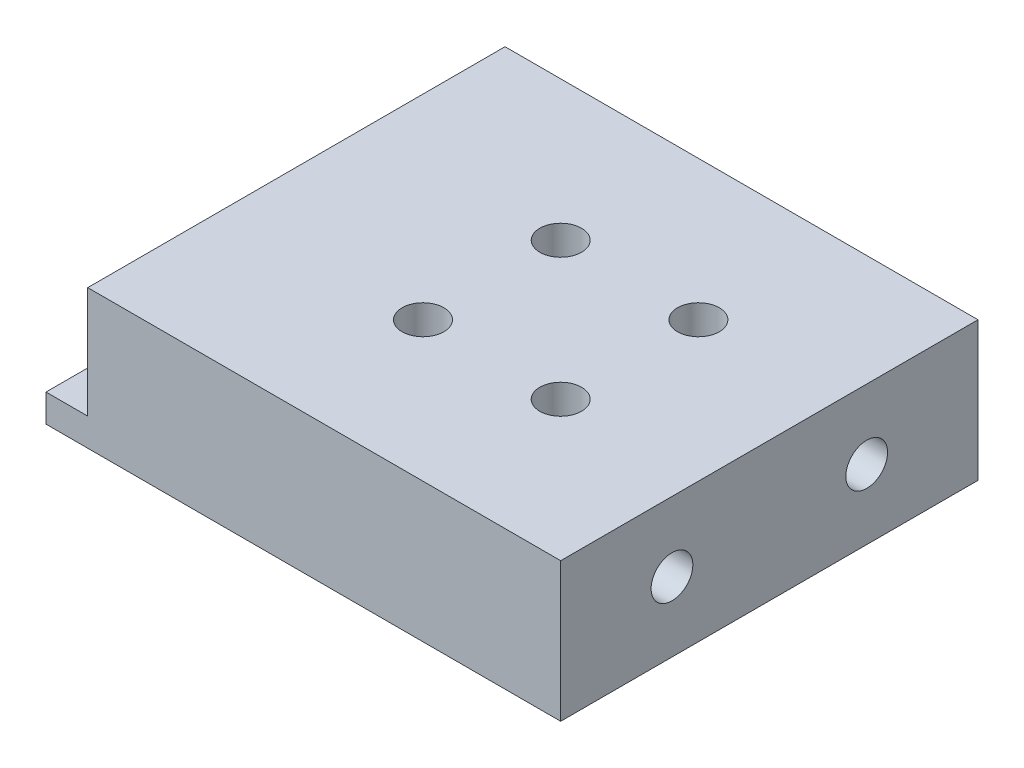
SolidWorks part; units mm, degrees
ref_plane "Спереди" through (0, 0, 0) normal (0, 0, 1) x (1, 0, 0)
ref_plane "Сверху" through (0, 0, 0) normal (0, 1, 0) x (1, 0, 0)
ref_plane "Справа" through (0, 0, 0) normal (1, 0, 0) x (0, 0, -1)
sketch "Эскиз1" plane through (0, 0, 0) normal (0, 1, 0) x (1, 0, 0)
  line L0 (22, 15) -> (15.9896, 21.0104) construction
  line L1 (0, 0) -> (37, 0)
  line L2 (0, 0) -> (0, 30)
  line L3 (0, 30) -> (37, 30)
  line L4 (37, 0) -> (37, 30)
  line L5 (22, 15) -> (22, 25.5625) construction
  line L6 (22, 15) -> (28.0104, 21.0104) construction
  line L7 (22, 15) -> (28.0104, 8.9896) construction
  line L8 (22, 15) -> (15.9896, 8.9896) construction
  circle A0 centre (22, 15) radius 7 construction
  circle A1 centre (22, 15) radius 8.5 construction
  circle A2 centre (26.9497, 19.9497) radius 1.5
  circle A3 centre (17.0503, 19.9497) radius 1.5
  circle A4 centre (26.9497, 10.0503) radius 1.5
  circle A5 centre (17.0503, 10.0503) radius 1.5
  dimension "D3" = 15
  dimension "D5" = 14
  dimension "D6" = 17
  dimension "D1" = 37
  dimension "D2" = 30
  dimension "D4" = 15
  dimension "D7" = 45
extrude "Бобышка-Вытянуть1" add sketch "Эскиз1" along normal blind 10
sketch "Эскиз2" plane through (37, 0, 0) normal (1, 0, 0) x (0, 0, -1)
  line L0 (0, 5) -> (30, 5) construction
  line L1 (0, 10) -> (0, 0) construction
  line L2 (30, 10) -> (30, 0) construction
  circle A0 centre (8, 5) radius 1.5
  circle A1 centre (22, 5) radius 1.5
  dimension "D1" = 3
  dimension "D2" = 3
  dimension "D3" = 8
  dimension "D4" = 14
extrude "Вырез-Вытянуть1" cut sketch "Эскиз2" against normal blind 6
sketch "Эскиз3" plane through (0, 0, 0) normal (-1, 0, 0) x (0, 0, 1)
  line L0 (-30, 10) -> (0, 10) construction
  line L1 (-30, 10) -> (0, 10)
  line L2 (-30, 10) -> (-30, 2)
  line L3 (-30, 2) -> (0, 2)
  line L4 (0, 10) -> (0, 2)
  line L5 (-30, 0) -> (0, 0) construction
  point P6 (-15, 10)
  point P9 (-15, 0)
  dimension "D1" = 8
  dimension "D2" = 30
extrude "Вырез-Вытянуть2" cut sketch "Эскиз3" against normal blind 3
sketch "Эскиз4" plane through (0, 0, 0) normal (-1, 0, 0) x (0, 0, 1)
  line L0 (-20, 5.4) -> (-9, 5.4) construction
  line L1 (0, 10) -> (-30, 10) construction
  line L2 (-20, 4.4) -> (-10, 4.4) construction
  circle A0 centre (-20, 5.4) radius 1
  circle A1 centre (-10, 5.4) radius 1
  point P5 (-15, 10)
  dimension "D1" = 5
  dimension "D2" = 2
  dimension "D3" = 10
  dimension "D4" = 4.6
extrude "Вырез-Вытянуть3" cut sketch "Эскиз4" against normal blind 7
